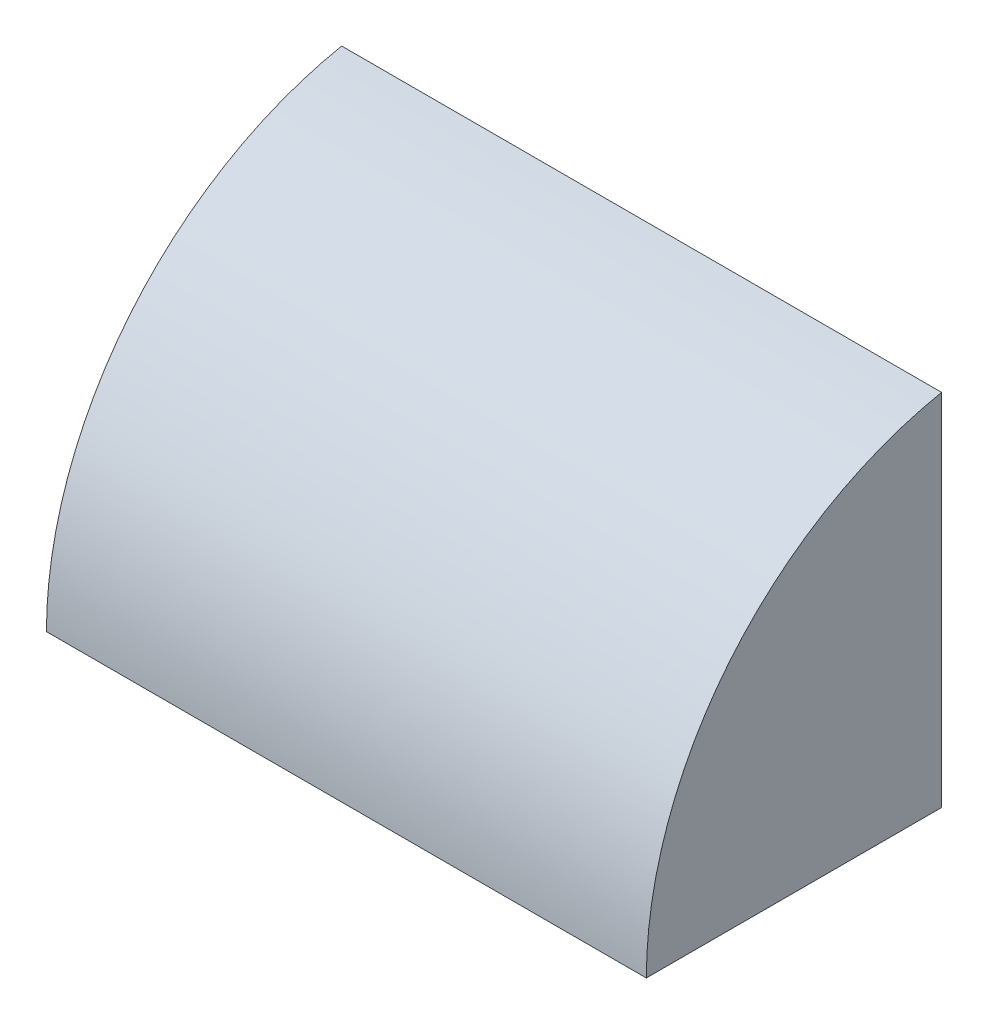
SolidWorks part; units mm, degrees
ref_plane "Front Plane" through (0, 0, 0) normal (0, 0, 1) x (1, 0, 0)
ref_plane "Top Plane" through (0, 0, 0) normal (0, 1, 0) x (1, 0, 0)
ref_plane "Right Plane" through (0, 0, 0) normal (1, 0, 0) x (0, 0, -1)
sketch "Sketch1" plane through (0, 0, 0) normal (1, 0, 0) x (0, 0, -1)
  line L0 (0, 9.5) -> (0, 0)
  line L1 (0, 0) -> (-7.8, 0)
  arc A0 (-7.8, 0) -> (0, 9.5) centre (1.8853, 0) cw
  dimension "D1" = 9.5
  dimension "D2" = 7.8
extrude "Boss-Extrude1" add sketch "Sketch1" against normal blind 15.85
shell "Shell1" thickness 1.5
